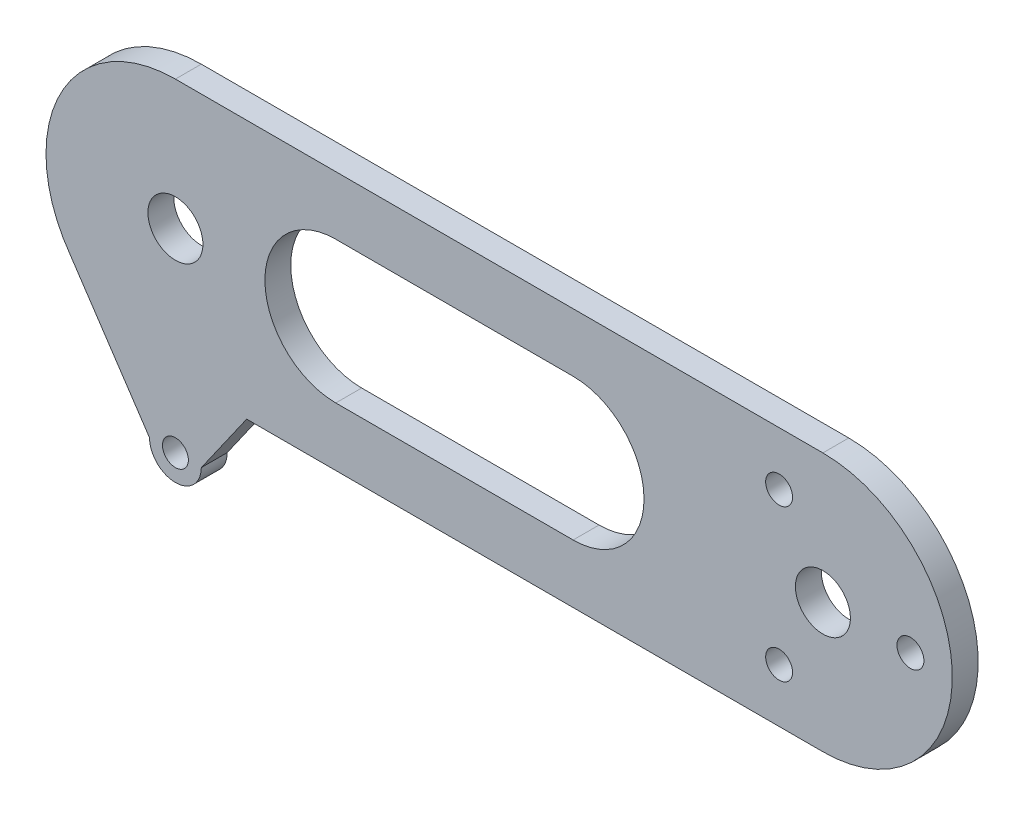
SolidWorks part; units mm, degrees
ref_plane "前视基准面" through (0, 0, 0) normal (0, 0, 1) x (1, 0, 0)
ref_plane "上视基准面" through (0, 0, 0) normal (0, 1, 0) x (1, 0, 0)
ref_plane "右视基准面" through (0, 0, 0) normal (1, 0, 0) x (0, 0, -1)
sketch "草图1" plane through (0, 0, 0) normal (0, 0, 1) x (1, 0, 0)
  line L0 (-1, 20) -> (99.0643, 20)
  line L7 (23.7835, 0) -> (60.4665, 0) construction
  line L12 (23.7835, 10.9539) -> (60.4665, 10.9539)
  line L13 (23.7835, -10.9539) -> (60.4665, -10.9539)
  line L19 (-1, 0) -> (-1, -30) construction
  line L20 (-5, -30) -> (-17.2082, -11.7173)
  line L59 (0, 32.5) -> (-18, 32.5) construction
  line L61 (3, -30) -> (10.0145, -20)
  line L62 (10.0145, -20) -> (99.0643, -20)
  line L84 (-1, 0) -> (85.25, 0) construction
  circle A0 centre (-1, 0) radius 4.25
  arc A9 (-1, 20) -> (-1, -20) centre (-1, 0) ccw construction
  circle A13 centre (99.0643, 0) radius 4.25
  circle A18 centre (99.0643, 0) radius 13.53 construction
  arc A22 (99.0643, 20) -> (99.0643, -20) centre (99.0643, 0) cw
  arc A25 (23.7835, 10.9539) -> (23.7835, -10.9539) centre (23.7835, 0) ccw
  arc A26 (60.4665, -10.9539) -> (60.4665, 10.9539) centre (60.4665, 0) ccw
  circle A27 centre (112.5943, 0) radius 2.08
  circle A28 centre (92.2993, -11.7173) radius 2.08
  circle A29 centre (92.2993, 11.7173) radius 2.08
  circle A30 centre (-1, -30) radius 2
  circle A31 centre (-1, -30) radius 4 construction
  arc A32 (-17.2082, -11.7173) -> (-1, 20) centre (-1, 0) cw
  arc A33 (-5, -30) -> (3, -30) centre (-1, -30) ccw
  point P14 (42.125, 0)
  dimension "D1" = 8.5
  dimension "D2" = 3
  dimension "D3" = 8.5
extrude "凸台-拉伸1" add sketch "草图1" along normal blind 4
sketch "草图4" plane through (0, 0, 4) normal (0, 0, 1) x (1, 0, 0)
  circle A0 centre (-1, 0) radius 5
sketch "草图5" plane through (0, 0, 0) normal (0, 0, -1) x (-1, 0, 0)
  circle A0 centre (1, 0) radius 5
